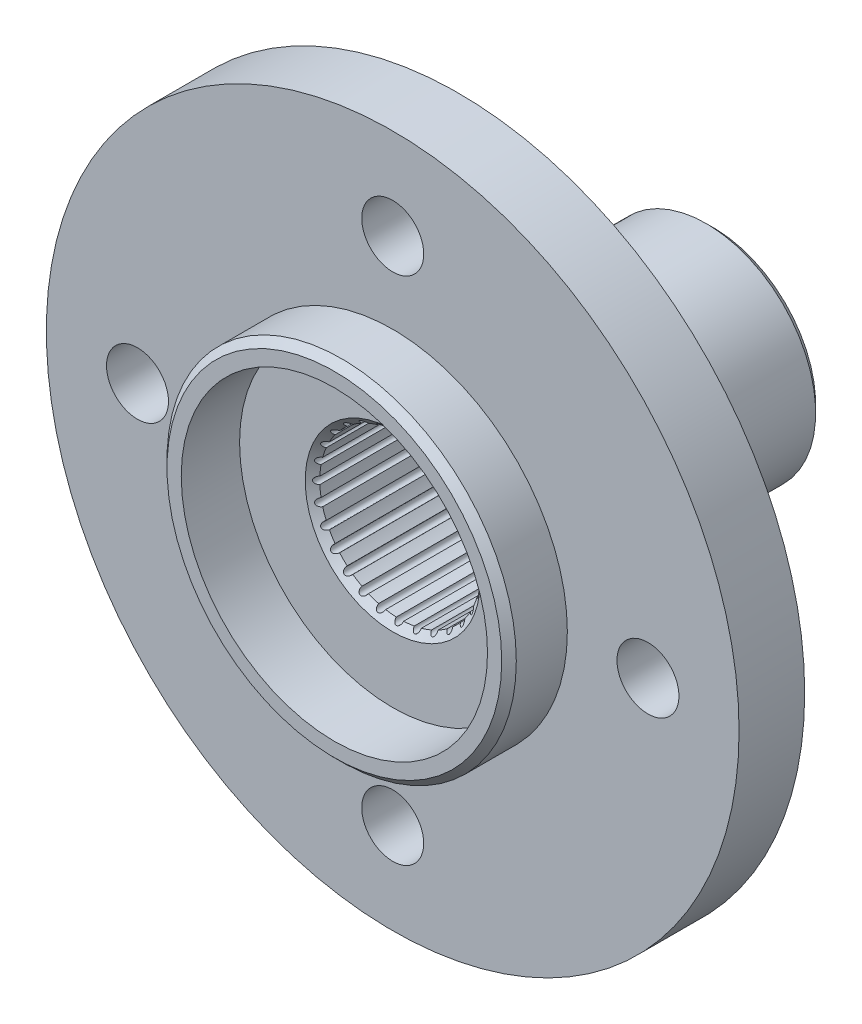
SolidWorks part; units mm, degrees
ref_plane "Ön Düzlem" through (0, 0, 0) normal (0, 0, 1) x (1, 0, 0)
ref_plane "Üst Düzlem" through (0, 0, 0) normal (0, 1, 0) x (1, 0, 0)
ref_plane "Sağ Düzlem" through (0, 0, 0) normal (1, 0, 0) x (0, 0, -1)
sketch "Sketch1" plane through (0, 0, 0) normal (0, 0, 1) x (1, 0, 0)
  circle A0 centre (0, 0) radius 47.5
  dimension "D1" = 95
extrude "Boss-Extrude1" add sketch "Sketch1" along normal blind 9
sketch "Sketch2" plane through (0, 0, 0) normal (0, 0, -1) x (-1, 0, 0)
  circle A0 centre (0, 0) radius 20
  dimension "D1" = 40
extrude "Boss-Extrude2" add sketch "Sketch2" along normal blind 6.2
sketch "Sketch3" plane through (0, 0, -6.2) normal (0, 0, -1) x (-1, 0, 0)
  circle A0 centre (0, 0) radius 15
  dimension "D1" = 30
extrude "Boss-Extrude3" add sketch "Sketch3" along normal blind 28.8
sketch "Sketch6" plane through (0, 0, -35) normal (0, 0, -1) x (-1, 0, 0)
  circle A0 centre (0, 0) radius 11
  dimension "D1" = 22
extrude "Cut-Extrude2" cut sketch "Sketch6" against normal blind 25
chamfer "Chamfer2" distance 1 1 edges at (-11, 0, -35)
sketch "Sketch9" plane through (0, 0, 9) normal (0, 0, 1) x (1, 0, 0)
  circle A0 centre (0, 35) radius 4.25
  circle A1 centre (35, 0) radius 4.25
  circle A2 centre (0, -35) radius 4.25
  circle A3 centre (-35, 0) radius 4.25
  point P12 (0, 0)
  dimension "D2" = 8.5
  dimension "D1" = 35
  dimension "D3" = 4
extrude "Cut-Extrude5" cut sketch "Sketch9" against normal up to next
chamfer "Chamfer3" distance 1 1 edges at (-15, 0, -35)
sketch "Sketch12" plane through (0, 0, 9) normal (0, 0, 1) x (1, 0, 0)
  circle A0 centre (0, 0) radius 23.95
  dimension "D1" = 47.9
extrude "Boss-Extrude4" add sketch "Sketch12" along normal blind 8
sketch "Sketch13" plane through (0, 0, 17) normal (0, 0, 1) x (1, 0, 0)
  circle A0 centre (0, 0) radius 21
  dimension "D1" = 42
extrude "Cut-Extrude6" cut sketch "Sketch13" against normal up to surface (8 mm away) up to face at (23.95, 0, 9)
chamfer "Chamfer4" distance 1 1 edges at (23.95, 0, 17)
sketch "Sketch8" plane through (0, 0, -35) normal (0, 0, -1) x (-1, 0, 0)
  circle A0 centre (0, 11) radius 0.5
  circle A1 centre (0, 0) radius 11 construction
  circle A2 centre (2.4477, 10.7242) radius 0.5
  circle A3 centre (4.7727, 9.9107) radius 0.5
  circle A4 centre (6.8584, 8.6001) radius 0.5
  circle A5 centre (8.6001, 6.8584) radius 0.5
  circle A6 centre (9.9107, 4.7727) radius 0.5
  circle A7 centre (10.7242, 2.4477) radius 0.5
  circle A8 centre (11, 0) radius 0.5
  circle A9 centre (10.7242, -2.4477) radius 0.5
  circle A10 centre (9.9107, -4.7727) radius 0.5
  circle A11 centre (8.6001, -6.8584) radius 0.5
  circle A12 centre (6.8584, -8.6001) radius 0.5
  circle A13 centre (4.7727, -9.9107) radius 0.5
  circle A14 centre (2.4477, -10.7242) radius 0.5
  circle A15 centre (0, -11) radius 0.5
  circle A16 centre (-2.4477, -10.7242) radius 0.5
  circle A17 centre (-4.7727, -9.9107) radius 0.5
  circle A18 centre (-6.8584, -8.6001) radius 0.5
  circle A19 centre (-8.6001, -6.8584) radius 0.5
  circle A20 centre (-9.9107, -4.7727) radius 0.5
  circle A21 centre (-10.7242, -2.4477) radius 0.5
  circle A22 centre (-11, 0) radius 0.5
  circle A23 centre (-10.7242, 2.4477) radius 0.5
  circle A24 centre (-9.9107, 4.7727) radius 0.5
  circle A25 centre (-8.6001, 6.8584) radius 0.5
  circle A26 centre (-6.8584, 8.6001) radius 0.5
  circle A27 centre (-4.7727, 9.9107) radius 0.5
  circle A28 centre (-2.4477, 10.7242) radius 0.5
  point P61 (0, 0)
  dimension "D1" = 1
  dimension "D2" = 28
extrude "Cut-Extrude4" cut sketch "Sketch8" against normal up to surface (25 mm away) up to face at (-11, 0, -10)
sketch "Sketch14" plane through (0, 0, -10) normal (0, 0, -1) x (-1, 0, 0)
  circle A0 centre (0, 0) radius 11
extrude "Cut-Extrude7" cut sketch "Sketch14" against normal through all
chamfer "Chamfer5" distance 1 1 edges at (11, 0, 9)
sketch "Sketch15" plane through (0, 0, -35) normal (0, 0, -1) x (-1, 0, 0)
  circle A1 centre (8.6001, 6.8584) radius 0.5
  circle A2 centre (8.6001, 6.8584) radius 0.5
  circle A3 centre (6.8584, 8.6001) radius 0.5
  circle A4 centre (6.8584, 8.6001) radius 0.5
  circle A5 centre (4.7727, 9.9107) radius 0.5
  circle A6 centre (4.7727, 9.9107) radius 0.5
  circle A7 centre (2.4477, 10.7242) radius 0.5
  circle A8 centre (2.4477, 10.7242) radius 0.5
  circle A9 centre (0, 11) radius 0.5
  circle A10 centre (0, 11) radius 0.5
  circle A11 centre (4.7727, -9.9107) radius 0.5
  circle A12 centre (4.7727, -9.9107) radius 0.5
  circle A13 centre (6.8584, -8.6001) radius 0.5
  circle A14 centre (6.8584, -8.6001) radius 0.5
  circle A15 centre (8.6001, -6.8584) radius 0.5
  circle A16 centre (8.6001, -6.8584) radius 0.5
  circle A17 centre (9.9107, -4.7727) radius 0.5
  circle A18 centre (9.9107, -4.7727) radius 0.5
  circle A19 centre (10.7242, -2.4477) radius 0.5
  circle A20 centre (10.7242, -2.4477) radius 0.5
  circle A21 centre (11, 0) radius 0.5
  circle A22 centre (11, 0) radius 0.5
  circle A23 centre (10.7242, 2.4477) radius 0.5
  circle A24 centre (10.7242, 2.4477) radius 0.5
  circle A25 centre (9.9107, 4.7727) radius 0.5
  circle A26 centre (9.9107, 4.7727) radius 0.5
  circle A27 centre (-10.7242, -2.4477) radius 0.5
  circle A28 centre (-10.7242, -2.4477) radius 0.5
  circle A29 centre (-9.9107, -4.7727) radius 0.5
  circle A30 centre (-9.9107, -4.7727) radius 0.5
  circle A31 centre (-8.6001, -6.8584) radius 0.5
  circle A32 centre (-8.6001, -6.8584) radius 0.5
  circle A33 centre (-6.8584, -8.6001) radius 0.5
  circle A34 centre (-6.8584, -8.6001) radius 0.5
  circle A35 centre (-4.7727, -9.9107) radius 0.5
  circle A36 centre (-4.7727, -9.9107) radius 0.5
  circle A37 centre (-2.4477, -10.7242) radius 0.5
  circle A38 centre (-2.4477, -10.7242) radius 0.5
  circle A39 centre (0, -11) radius 0.5
  circle A40 centre (0, -11) radius 0.5
  circle A41 centre (2.4477, -10.7242) radius 0.5
  circle A42 centre (2.4477, -10.7242) radius 0.5
  circle A43 centre (-2.4477, 10.7242) radius 0.5
  circle A44 centre (-2.4477, 10.7242) radius 0.5
  circle A45 centre (-4.7727, 9.9107) radius 0.5
  circle A46 centre (-4.7727, 9.9107) radius 0.5
  circle A47 centre (-6.8584, 8.6001) radius 0.5
  circle A48 centre (-6.8584, 8.6001) radius 0.5
  circle A49 centre (-8.6001, 6.8584) radius 0.5
  circle A50 centre (-8.6001, 6.8584) radius 0.5
  circle A51 centre (-9.9107, 4.7727) radius 0.5
  circle A52 centre (-9.9107, 4.7727) radius 0.5
  circle A53 centre (-10.7242, 2.4477) radius 0.5
  circle A54 centre (-10.7242, 2.4477) radius 0.5
  circle A55 centre (-11, 0) radius 0.5
  circle A56 centre (-11, 0) radius 0.5
  dimension "D1" = 0
  dimension "D2" = 0
  dimension "D3" = 0
  dimension "D4" = 0
  dimension "D5" = 0
  dimension "D6" = 0
  dimension "D7" = 0
  dimension "D8" = 0
  dimension "D9" = 0
  dimension "D10" = 0
  dimension "D11" = 0
  dimension "D12" = 0
  dimension "D13" = 0
  dimension "D14" = 0
  dimension "D15" = 0
  dimension "D16" = 0
  dimension "D17" = 0
  dimension "D18" = 0
  dimension "D19" = 0
  dimension "D20" = 0
  dimension "D21" = 0
  dimension "D22" = 0
  dimension "D23" = 0
  dimension "D24" = 0
  dimension "D25" = 0
  dimension "D26" = 0
  dimension "D27" = 0
  dimension "D28" = 0
extrude "Cut-Extrude8" cut sketch "Sketch15" against normal through all
fillet "Fillet1" radius 2 2 edges at (-20, 0, 0) (-20, 0, -6.2)
